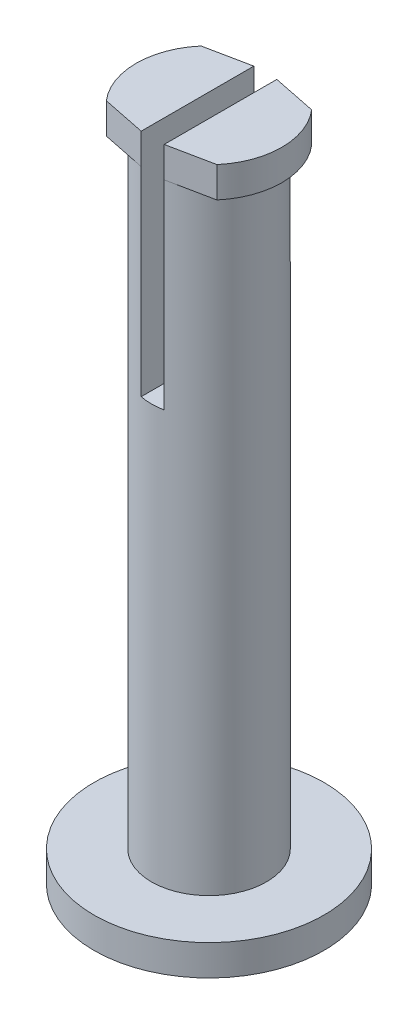
SolidWorks part; units mm, degrees
material "PLA (Polylactic Acid)"
ref_plane "Front" through (0, 0, 0) normal (0, 0, 1) x (1, 0, 0)
ref_plane "Top" through (0, 0, 0) normal (0, 1, 0) x (1, 0, 0)
ref_plane "Right" through (0, 0, 0) normal (1, 0, 0) x (0, 0, -1)
sketch "Sketch1" plane through (0, 0, 0) normal (0, 1, 0) x (1, 0, 0)
  circle A0 centre (0, 0) radius 3.75
  dimension "D1" = 7.5
extrude "Boss-Extrude1" add sketch "Sketch1" along normal blind 1
sketch "Sketch2" plane through (0, 1, 0) normal (0, 1, 0) x (1, 0, 0)
  circle A0 centre (0, 0) radius 1.875
  dimension "D1" = 3.75
extrude "Boss-Extrude2" add sketch "Sketch2" along normal blind 20
sketch "Sketch3" plane through (0, 21, 0) normal (0, 1, 0) x (1, 0, 0)
  circle A0 centre (0, 0) radius 2.375
  circle A1 centre (0, 0) radius 1.875 construction
  dimension "D1" = 0.5
extrude "Boss-Extrude3" add sketch "Sketch3" along normal blind 1
sketch "Sketch4" plane through (0, 22, 0) normal (0, 1, 0) x (1, 0, 0)
  line L1 (0.375, -4) -> (-0.375, -4)
  line L2 (0.375, -4) -> (0.375, 4)
  line L3 (0.375, 4) -> (-0.375, 4)
  line L4 (-0.375, -4) -> (-0.375, 4)
  line L5 (0.375, -4) -> (-0.375, 4) construction
  line L6 (0.375, 4) -> (-0.375, -4) construction
  point P0 (0, 0)
  dimension "D1" = 0.75
  dimension "D2" = 8
extrude "Cut-Extrude1" cut sketch "Sketch4" against normal blind 7.5
sketch "Sketch5" plane through (0, 22, 0) normal (0, 1, 0) x (1, 0, 0)
  line L0 (0.375, -1.8371) -> (1.8033, -1.5456)
  line L1 (0.375, -2.3452) -> (0.375, 2.3452) construction
  line L2 (0.375, 1.8371) -> (1.8033, 1.5456)
  line L3 (-0.375, 1.8371) -> (-1.8033, 1.5456)
  line L4 (-0.375, 2.3452) -> (-0.375, -2.3452) construction
  line L5 (-0.375, -1.8371) -> (-1.8033, -1.5456)
  line L6 (0.375, 2.3452) -> (0.375, -2.3452) construction
  line L7 (-0.375, -2.3452) -> (-0.375, 2.3452) construction
  line L8 (0.375, 2.3452) -> (0.375, -2.3452)
  line L9 (-0.375, -2.3452) -> (-0.375, 2.3452)
  circle A0 centre (0, 0) radius 1.875
  arc A1 (0.375, -2.3452) -> (0.375, 2.3452) centre (0, 0) ccw construction
  arc A2 (-0.375, 2.3452) -> (-0.375, -2.3452) centre (0, 0) ccw construction
  arc A3 (0.375, -2.3452) -> (0.375, 2.3452) centre (0, 0) ccw
  arc A4 (-0.375, 2.3452) -> (-0.375, -2.3452) centre (0, 0) ccw
  line M4 (0.375, 2.3452) -> (0.375, -2.3452)
  arc M5 (0.375, -2.3452) -> (0.375, 2.3452) centre (0, 0) ccw
  dimension "D1" = 0.5
extrude "Cut-Extrude2" cut sketch "Sketch5" against normal blind 10 contours L0 M4 M5 | L2 M4 M5 | L9 A4 L3 | L5 A4 L9
